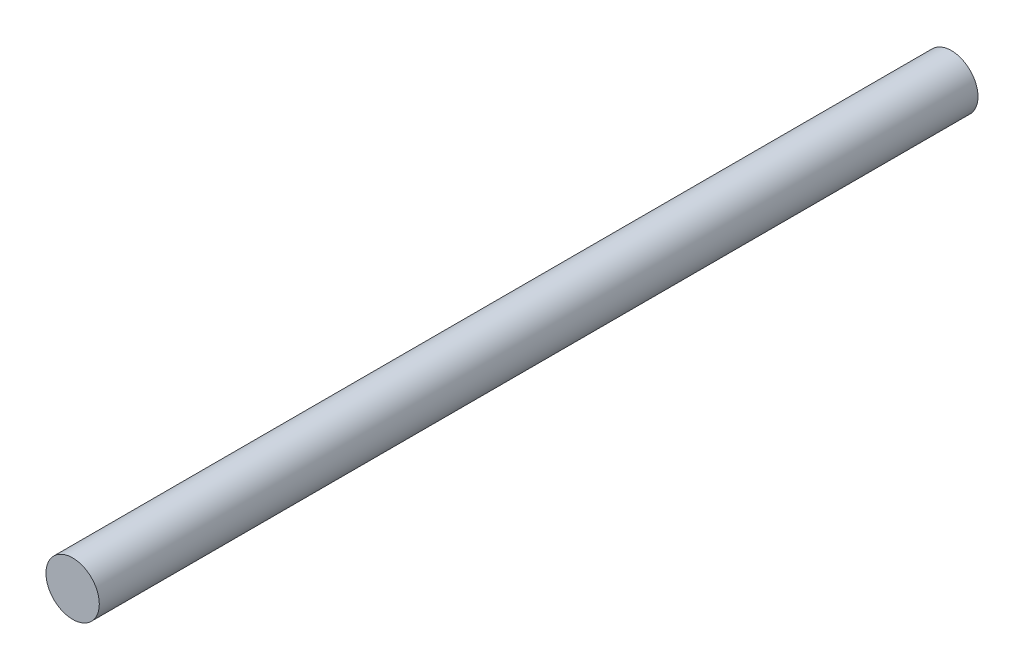
SolidWorks part; units mm, degrees
ref_plane "Plan de face" through (0, 0, 0) normal (0, 0, 1) x (1, 0, 0)
ref_plane "Plan de dessus" through (0, 0, 0) normal (0, 1, 0) x (1, 0, 0)
ref_plane "Plan de droite" through (0, 0, 0) normal (1, 0, 0) x (0, 0, -1)
sketch "Esquisse1" plane through (0, 0, 0) normal (0, 0, 1) x (1, 0, 0)
  circle A0 centre (0, 0) radius 8.5
extrude "Boss.-Extru.1" add sketch "Esquisse1" along normal blind 280
